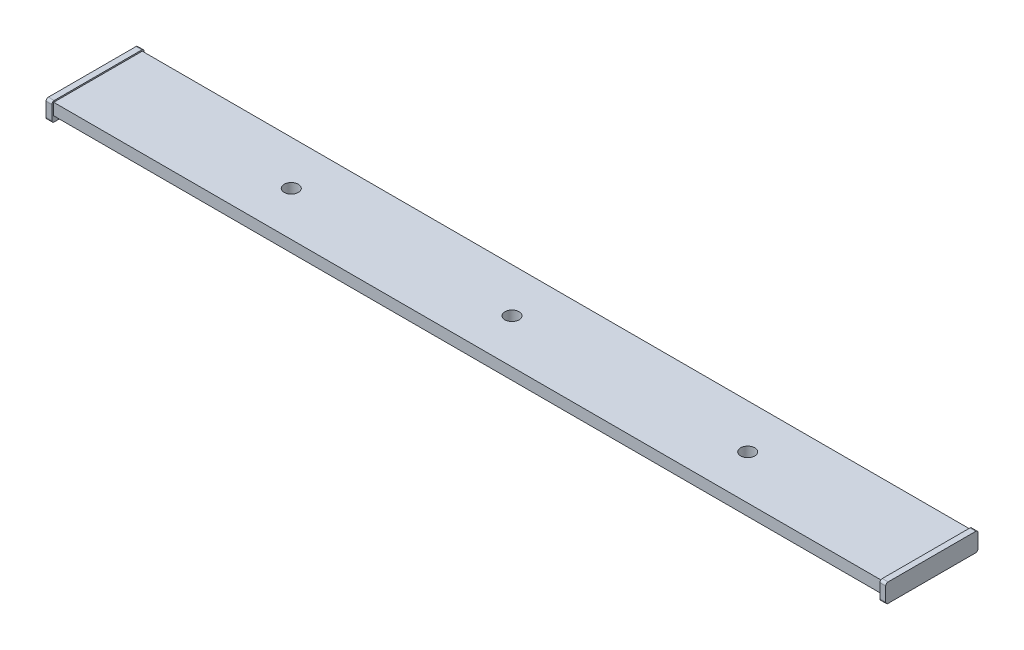
SolidWorks part; units mm, degrees
ref_plane "Front Plane" through (0, 0, 0) normal (0, 0, 1) x (1, 0, 0)
ref_plane "Top Plane" through (0, 0, 0) normal (0, 1, 0) x (1, 0, 0)
ref_plane "Right Plane" through (0, 0, 0) normal (1, 0, 0) x (0, 0, -1)
sketch "Sketch1" plane through (0, 0, 0) normal (0, 1, 0) x (1, 0, 0)
  line L1 (-1800, -189.8438) -> (1800, -189.8438)
  line L2 (-1800, -189.8438) -> (-1800, 189.8438)
  line L3 (-1800, 189.8438) -> (1800, 189.8438)
  line L4 (1800, -189.8438) -> (1800, 189.8438)
  line L5 (-1800, -189.8438) -> (1800, 189.8438) construction
  line L6 (-1800, 189.8438) -> (1800, -189.8438) construction
  point P0 (0, 0)
  dimension "D1" = 3600
extrude "Boss-Extrude1" add sketch "Sketch1" along normal blind 50
sketch "Sketch2" plane through (0, 0, 0) normal (0, -1, 0) x (1, 0, 0)
  line L0 (-1800, -189.8438) -> (-1800, 189.8438) construction
  line L1 (1853.8514, 157.6118) -> (-1800, 157.6118)
  line L2 (1853.8514, 157.6118) -> (1853.8514, 142.6118)
  line L3 (1853.8514, 142.6118) -> (-1800, 142.6118)
  line L4 (-1800, 157.6118) -> (-1800, 142.6118)
  line L5 (1853.8514, 157.6118) -> (-1800, 142.6118) construction
  line L6 (1853.8514, 142.6118) -> (-1800, 157.6118) construction
  line L7 (27.5, 0) -> (-27.5, 0) construction
  line L8 (1853.8514, -157.6118) -> (1853.8514, -142.6118)
  line L9 (-1800, -157.6118) -> (-1800, -142.6118)
  line L10 (1853.8514, -142.6118) -> (-1800, -142.6118)
  line L11 (1853.8514, -157.6118) -> (-1800, -157.6118)
  point P0 (26.9257, 150.1118)
  dimension "D1" = 150
  dimension "D2" = 15
extrude "Cut-Extrude1" cut sketch "Sketch2" against normal blind 25
sketch "Sketch3" plane through (0, 0, 0) normal (0, -1, 0) x (1, 0, 0)
  circle A0 centre (0, 0) radius 30.3811
  circle A1 centre (-946.3055, 0) radius 30.3811
  circle A2 centre (1010.6037, 0) radius 30.3811
extrude "Cut-Extrude2" cut sketch "Sketch3" against normal through all
sketch "Sketch4" plane through (1800, 0, 0) normal (1, 0, 0) x (0, 0, -1)
  line L1 (-187.8144, -24.1905) -> (187.8144, -24.1905)
  line L2 (-197.8144, -14.1905) -> (-197.8144, 45.6812)
  line L3 (-187.8144, 55.6812) -> (187.8144, 55.6812)
  line L4 (197.8144, -14.1905) -> (197.8144, 45.6812)
  line L5 (-197.8144, -24.1905) -> (197.8144, 55.6812) construction
  line L6 (-197.8144, 55.6812) -> (197.8144, -24.1905) construction
  arc A0 (187.8144, -24.1905) -> (197.8144, -14.1905) centre (187.8144, -14.1905) ccw
  arc A1 (187.8144, 55.6812) -> (197.8144, 45.6812) centre (187.8144, 45.6812) cw
  arc A2 (-187.8144, -24.1905) -> (-197.8144, -14.1905) centre (-187.8144, -14.1905) cw
  arc A3 (-197.8144, 45.6812) -> (-187.8144, 55.6812) centre (-187.8144, 45.6812) cw
  point P0 (0, 15.7454)
  point P17 (0, 36.963)
  dimension "D1" = 10
extrude "Boss-Extrude2" add sketch "Sketch4" against normal blind 25
mirror "Mirror1" about plane through (0, 0, 0) normal (1, 0, 0) of "Boss-Extrude2"
